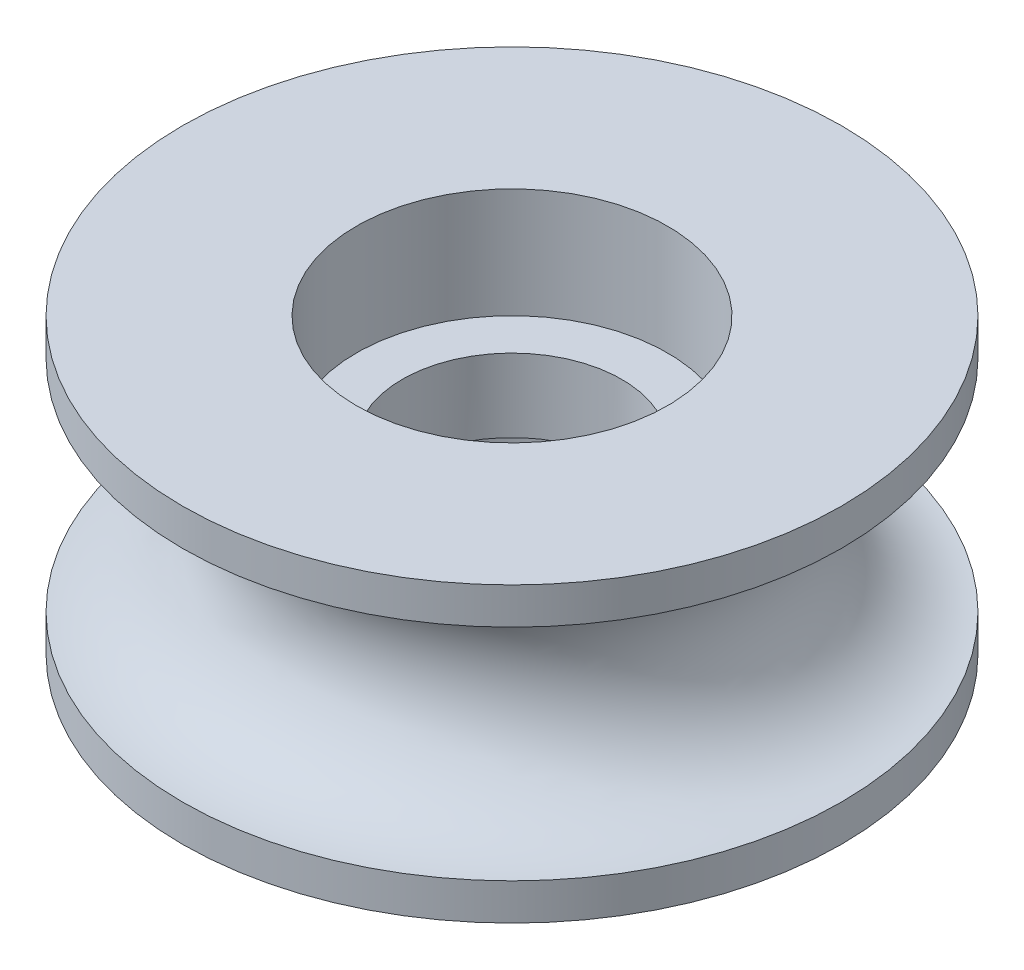
SolidWorks part; units mm, degrees
ref_plane "前视基准面" through (0, 0, 0) normal (0, 0, 1) x (1, 0, 0)
ref_plane "上视基准面" through (0, 0, 0) normal (0, 1, 0) x (1, 0, 0)
ref_plane "右视基准面" through (0, 0, 0) normal (1, 0, 0) x (0, 0, -1)
sketch "草图1" plane through (0, 0, 0) normal (0, 1, 0) x (1, 0, 0)
  circle A0 centre (0, 0) radius 9
  dimension "D1" = 18
extrude "凸台-拉伸1" add sketch "草图1" along normal blind 8
sketch "草图2" plane through (0, 8, 0) normal (0, 1, 0) x (1, 0, 0)
  circle A0 centre (0, 0) radius 3
  dimension "D1" = 6
ref_plane "基准面1" through (0, 4, 0) normal (0, 1, 0) x (1, 0, 0)
sketch "草图5" plane through (0, 0, 0) normal (1, 0, 0) x (0, 0, -1)
  line L0 (0, 8) -> (0, 0) construction
  line L1 (9, 8) -> (-9, 8) construction
  line L2 (9, 4) -> (0, 4) construction
  line L3 (9, 0) -> (9, 8) construction
  circle A0 centre (9, 4) radius 3
  dimension "D1" = 1
revolve "切除-旋转1" cut sketch "草图5" angle 360 about L0
ref_plane "基准面2" through (0, 4, 0) normal (0, -1, 0) x (-1, 0, 0)
extrude "切除-拉伸1" cut sketch "草图2" against normal through all
sketch "草图6" plane through (0, 8, 0) normal (0, 1, 0) x (1, 0, 0)
  circle A0 centre (0, 0) radius 4.25
  dimension "D1" = 8.5
extrude "切除-拉伸2" cut sketch "草图6" against normal blind 3
mirror "镜向2" about plane through (0, 4, 0) normal (0, -1, 0) of "切除-拉伸2"
sketch "草图8" plane through (0, 0, 0) normal (0, 0, 1) x (1, 0, 0)
  line L0 (0, 8) -> (0, 0) construction
  line L1 (9, 8) -> (-9, 8) construction
  circle A0 centre (0, 4) radius 1.5
  dimension "D1" = 3
split line "分割线1"
